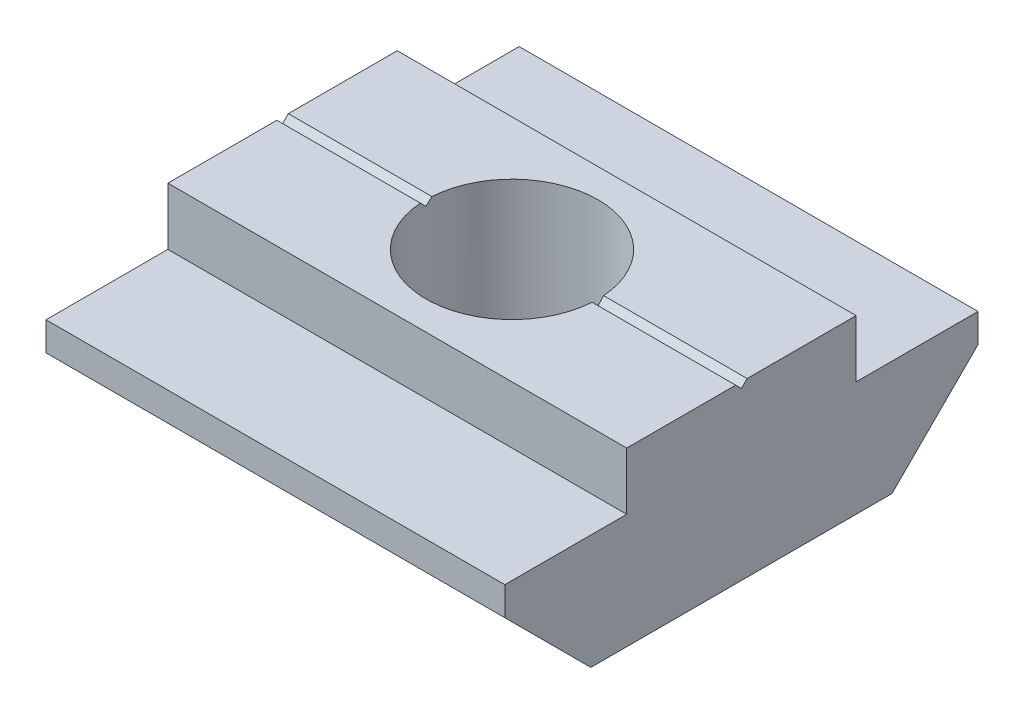
SolidWorks part; units mm, degrees
ref_plane "Front Plane" through (0, 0, 0) normal (0, 0, 1) x (1, 0, 0)
ref_plane "Top Plane" through (0, 0, 0) normal (0, 1, 0) x (1, 0, 0)
ref_plane "Right Plane" through (0, 0, 0) normal (1, 0, 0) x (0, 0, -1)
ref_plane "Plane1" through (8, 0, 0) normal (1, 0, 0) x (0, 0, -1)
sketch "Sketch1" plane through (8, 0, 0) normal (1, 0, 0) x (0, 0, -1)
  line L0 (-0.2, 0) -> (-4, 0)
  line L1 (-4, 0) -> (-4, -2)
  line L2 (-4, -2) -> (-8.25, -2)
  line L3 (-8.25, -2) -> (-8.25, -3)
  line L4 (-8.25, -3) -> (-5.25, -6)
  line L5 (-5.25, -6) -> (5.25, -6)
  line L6 (5.25, -6) -> (8.25, -3)
  line L7 (8.25, -3) -> (8.25, -2)
  line L8 (8.25, -2) -> (4, -2)
  line L9 (4, -2) -> (4, 0)
  line L10 (4, 0) -> (0.2, 0)
  line L11 (0.2, 0) -> (0, -0.2)
  line L12 (0, -0.2) -> (-0.2, 0)
extrude "Boss-Extrude1" add sketch "Sketch1" against normal blind 16
hole_wizard "Ø6.0 (6) Diameter Hole1" positions "Sketch3" profile "Sketch2" hole size "Ø6.0" standard "Ansi Metric"
sketch "Sketch3" plane through (0, -6, 0) normal (0, -1, 0) x (1, 0, 0)
  point P0 (0, 0)
sketch "Sketch2" plane through (0, -6, 0) normal (1, 0, 0) x (0, 0, -1)
  line L0 (0, 0) -> (0, 6)
  line L1 (0, 6) -> (3, 6)
  line L2 (3, 6) -> (3, 0)
  line L5 (3, 0) -> (0, 0)
  line L11 (0, -6.35) -> (0, 107.95) construction
  dimension "Thru Hole Dia." = 6
  dimension "Thru Hole Depth" = 6
